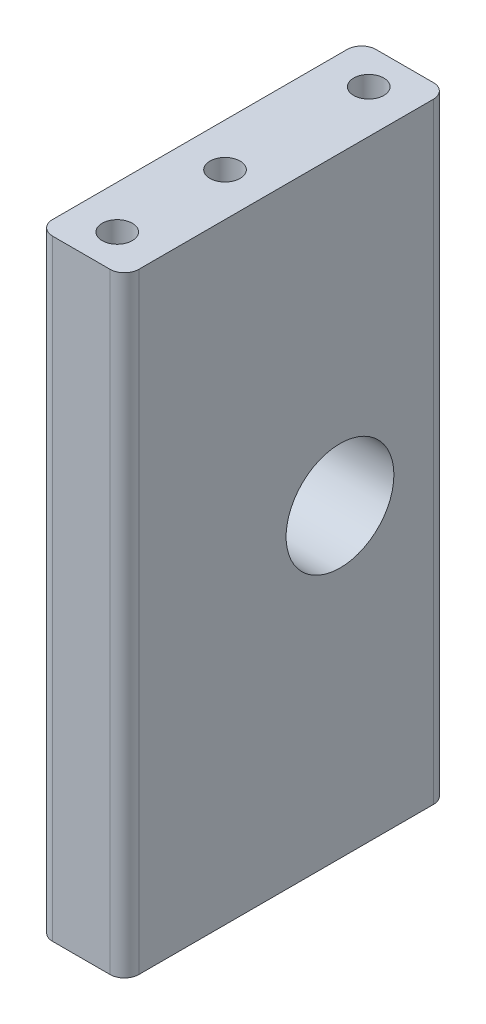
SolidWorks part; units mm, degrees
material "ABS"
ref_plane "Front Plane" through (0, 0, 0) normal (0, 0, 1) x (1, 0, 0)
ref_plane "Top Plane" through (0, 0, 0) normal (0, 1, 0) x (1, 0, 0)
ref_plane "Right Plane" through (0, 0, 0) normal (1, 0, 0) x (0, 0, -1)
sketch "Sketch1" plane through (0, 0, 0) normal (0, 1, 0) x (1, 0, 0)
  line L0 (0, 10) -> (0, -10) construction
  line L1 (-6, 30) -> (6, 30)
  line L2 (-6, 30) -> (-6, -30)
  line L3 (-6, -30) -> (6, -30)
  line L4 (6, 30) -> (6, -30)
  line L5 (0, 25) -> (0, -25) construction
  line L6 (6, 15) -> (-6, 15)
  circle A0 centre (0, 10) radius 2.5 construction
  circle A1 centre (0, -10) radius 2.5 construction
  circle A2 centre (0, 25) radius 2.5 construction
  circle A3 centre (0, -25) radius 2.5 construction
  point P8 (0, 30)
  point P9 (0, 0)
  point P10 (-6, 0)
  point P16 (0, 0)
  dimension "D2" = 5
  dimension "D1" = 20
  dimension "D3" = 12
  dimension "D4" = 60
  dimension "D5" = 50
  dimension "D6" = 5
extrude "Boss-Extrude1" add sketch "Sketch1" against normal blind 85 contours L4 L6 L2 L3
hole_wizard "Tap Drill for M5x0.8 Tap1" positions "3DSketch1" profile "Sketch2" hole size "M5x0.8" standard "ANSI Metric" end condition up to next
sketch3d "3DSketch1"
  point P19 (0, 0, -10)
  point P21 (0, 0, 10)
  point P23 (0, 0, 25)
sketch "Sketch2" plane through (0, 0, -10) normal (1, 0, 0) x (0, 0, 1)
  line L0 (0, 0) -> (0, 85)
  line L1 (0, 85) -> (2.1, 85)
  line L2 (2.1, 85) -> (2.1, 0)
  line L5 (2.1, 0) -> (0, 0)
  line L11 (0, -6.35) -> (0, 107.95) construction
  dimension "Thru Hole Dia." = 4.2
  dimension "Thru Hole Depth" = 85
sketch "Sketch3" plane through (6, 0, 0) normal (1, 0, 0) x (0, 0, -1)
  line L4 (15, 0) -> (-30, 0)
  line L5 (-30, 0) -> (-30, -85)
  line L6 (15, 0) -> (-30, 0)
  line L7 (-30, -85) -> (15, -85)
  line L9 (-30, 0) -> (-30, -85)
  line L12 (-30, -85) -> (15, -85)
  line L13 (15, -85) -> (15, 0)
  line L14 (15, -85) -> (15, 0)
  circle A0 centre (0, -42.5) radius 7.5
  point P8 (-30, -42.5)
  dimension "D2" = 15
  dimension "D1" = 0
extrude "Cut-Extrude1" cut sketch "Sketch3" against normal up to next contours A0
fillet "Fillet1" radius 2 4 edges at (-6, -42.5, 30) (6, -42.5, 30) (-6, -42.5, -15) (6, -42.5, -15)
